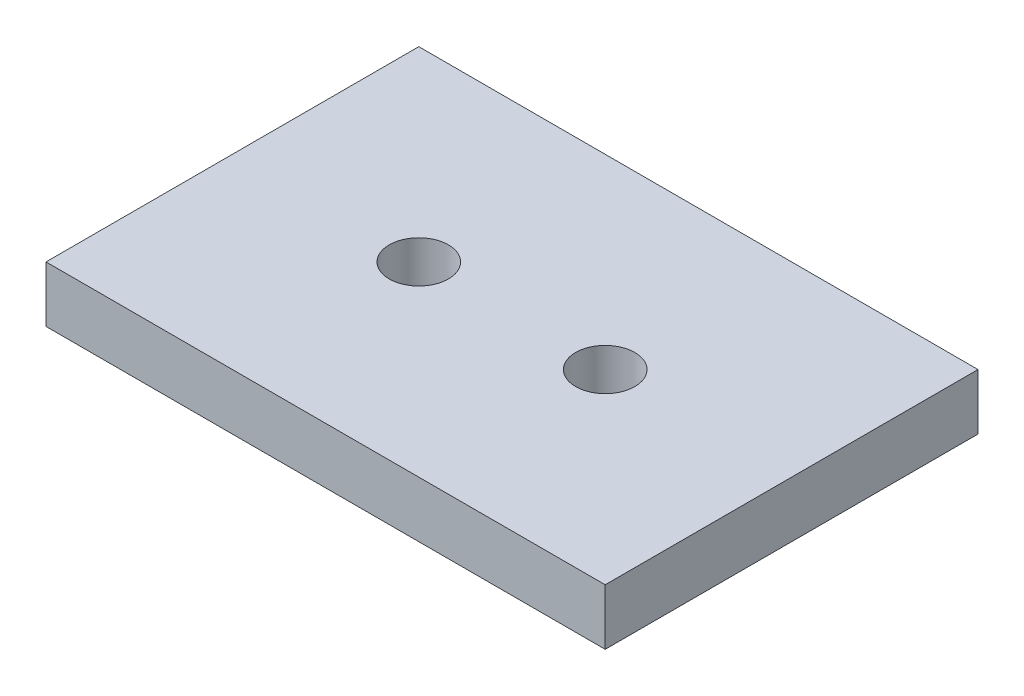
SolidWorks part; units mm, degrees
ref_plane "Front Plane" through (0, 0, 0) normal (0, 0, 1) x (1, 0, 0)
ref_plane "Top Plane" through (0, 0, 0) normal (0, 1, 0) x (1, 0, 0)
ref_plane "Right Plane" through (0, 0, 0) normal (1, 0, 0) x (0, 0, -1)
sketch "Sketch1" plane through (0, 0, 0) normal (0, 1, 0) x (1, 0, 0)
  line L0 (-15, 0) -> (15, 0)
  line L1 (-15, 10) -> (15, 10)
  line L2 (-15, 10) -> (-15, -10)
  line L3 (-15, -10) -> (15, -10)
  line L4 (15, 10) -> (15, -10)
  line L5 (-15, 10) -> (15, -10) construction
  line L6 (-15, -10) -> (15, 10) construction
  line L7 (0, 0) -> (0, -10) construction
  circle A0 centre (-5, 0) radius 1.5875
  circle A1 centre (5, 0) radius 1.5875
  point P0 (0, 0)
  dimension "D3" = 3.175
  dimension "D1" = 30
  dimension "D2" = 20
  dimension "D4" = 5
extrude "Boss-Extrude1" add sketch "Sketch1" along normal blind 3 contours L0 A1 A0 L2 L3 L4 | L0 A1 L4 L1 L2 A0
